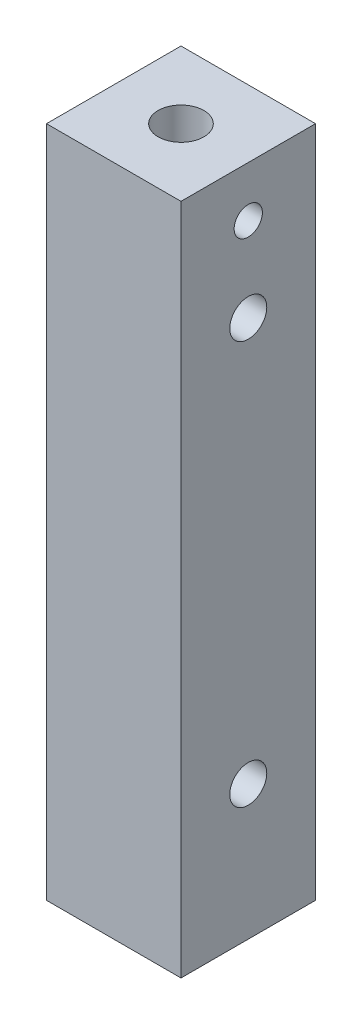
SolidWorks part; units mm, degrees
ref_plane "Front" through (0, 0, 0) normal (0, 0, 1) x (1, 0, 0)
ref_plane "Top" through (0, 0, 0) normal (0, 1, 0) x (1, 0, 0)
ref_plane "Right" through (0, 0, 0) normal (1, 0, 0) x (0, 0, -1)
sketch "Sketch1" plane through (0, 0, 0) normal (0, 1, 0) x (1, 0, 0)
  line L1 (0, 0) -> (20, 0)
  line L2 (0, 0) -> (0, 20)
  line L3 (0, 20) -> (20, 20)
  line L4 (20, 0) -> (20, 20)
  dimension "D1" = 20
  dimension "D2" = 20
extrude "Boss-Extrude1" add sketch "Sketch1" along normal blind 100
hole_wizard "M8 Tapped Hole1" positions "Sketch4" profile "Sketch5" tap size "M8" standard "ISO"
sketch "Sketch4" plane through (0, 100, 0) normal (0, 1, 0) x (1, 0, 0)
  line L0 (0, 20) -> (20, 0) construction
  line L2 (0, 0) -> (20, 20) construction
  point P13 (10, 10)
sketch "Sketch5" plane through (10, 100, -10) normal (1, 0, 0) x (0, 0, 1)
  line L0 (0, 0) -> (0, 15.7929)
  line L1 (0, 15.7929) -> (3.4, 13.75)
  line L2 (3.4, 13.75) -> (3.4, 0)
  line L5 (3.4, 0) -> (0, 0)
  line L10 (0, 15.7929) -> (-3.4, 13.75) construction
  line L11 (0, -6.35) -> (0, 107.95) construction
  dimension "Tap Drill Dia." = 6.8
  dimension "Tap Drill Depth" = 13.75
  dimension "Drill Angle" = 118
cosmetic thread "Hole Thread1"
ref_plane "Plane1" through (0, 50, 0) normal (0, 1, 0) x (1, 0, 0)
mirror "Mirror1" about plane through (0, 50, 0) normal (0, 1, 0) of "M8 Tapped Hole1"
cosmetic thread "Hole Thread2" parameters "D1"=16, "D2"=8
hole_wizard "M5 Tapped Hole1" [suppressed] positions "Sketch6" profile "Sketch7" tap size "M5" standard "ISO"
sketch "Sketch6" plane through (0, 0, 0) normal (0, 0, 1) x (1, 0, 0)
  line L0 (10, 100) -> (10, 95.0401) construction
  line L1 (0, 100) -> (20, 100) construction
  point P0 (10, 80)
  dimension "D1" = 20
sketch "Sketch7" plane through (10, 80, 0) normal (1, 0, 0) x (0, -1, 0)
  line L0 (0, 0) -> (0, 13.6618)
  line L1 (0, 13.6618) -> (2.1, 12.4)
  line L2 (2.1, 12.4) -> (2.1, 0)
  line L5 (2.1, 0) -> (0, 0)
  line L10 (0, 13.6618) -> (-2.1, 12.4) construction
  line L11 (0, -6.35) -> (0, 107.95) construction
  dimension "Tap Drill Dia." = 4.2
  dimension "Tap Drill Depth" = 12.4
  dimension "Drill Angle" = 118
cosmetic thread "Hole Thread3" [suppressed] parameters "D1"=10, "D2"=5
hole_wizard "M5 Tapped Hole2" [suppressed] positions "Sketch8" profile "Sketch9" tap size "M5" standard "ISO"
sketch "Sketch8" plane through (20, 0, 0) normal (1, 0, 0) x (0, 0, -1)
  line L0 (10, 0) -> (10, 26.2195) construction
  line L1 (0, 0) -> (20, 0) construction
  point P7 (10, 7.5)
  dimension "D1" = 7.5
sketch "Sketch9" plane through (20, 7.5, -10) normal (0, 1, 0) x (0, 0, -1)
  line L0 (0, 0) -> (0, 13.6618)
  line L1 (0, 13.6618) -> (2.1, 12.4)
  line L2 (2.1, 12.4) -> (2.1, 0)
  line L5 (2.1, 0) -> (0, 0)
  line L10 (0, 13.6618) -> (-2.1, 12.4) construction
  line L11 (0, -6.35) -> (0, 107.95) construction
  dimension "Tap Drill Dia." = 4.2
  dimension "Tap Drill Depth" = 12.4
  dimension "Drill Angle" = 118
cosmetic thread "Hole Thread4" [suppressed] parameters "D1"=10, "D2"=5
hole_wizard "M5 Clearance Hole1" positions "Sketch10" profile "Sketch12" hole size "M5" standard "ISO" end condition through all
sketch "Sketch10" plane through (20, 0, 0) normal (1, 0, 0) x (0, 0, -1)
  line L0 (10, 100) -> (10, 0) construction
  line L1 (0, 100) -> (20, 100) construction
  line L2 (0, 0) -> (20, 0) construction
  line L7 (0, 50) -> (20, 50) construction
  line L8 (0, 100) -> (0, 0) construction
  line L9 (20, 100) -> (20, 0) construction
  point P9 (10, 80)
  point P28 (10, 20)
  dimension "D1" = 20
sketch "Sketch12" plane through (20, 20, -10) normal (0, 1, 0) x (0, 0, -1)
  line L0 (0, 0) -> (0, 20)
  line L1 (0, 20) -> (2.75, 20)
  line L2 (2.75, 20) -> (2.75, 0)
  line L5 (2.75, 0) -> (0, 0)
  line L11 (0, -6.35) -> (0, 107.95) construction
  dimension "Thru Hole Dia." = 5.5
  dimension "Thru Hole Depth" = 20
hole_wizard "M5 Tapped Hole3" positions "Sketch13" profile "Sketch14" tap size "M5" standard "ISO"
sketch "Sketch13" plane through (20, 0, 0) normal (1, 0, 0) x (0, 0, -1)
  line L0 (10, 100) -> (10, 64.5146) construction
  line L1 (0, 100) -> (20, 100) construction
  circle A0 centre (10, 80) radius 2.75 construction
  point P7 (10, 92.5)
  dimension "D1" = 12.5
cosmetic thread "Hole Thread5"
sketch "Sketch14" plane through (20, 92.5, -10) normal (0, 1, 0) x (0, 0, -1)
  line L0 (0, 0) -> (0, 11.6618)
  line L1 (0, 11.6618) -> (2.1, 10.4)
  line L2 (2.1, 10.4) -> (2.1, 0)
  line L5 (2.1, 0) -> (0, 0)
  line L10 (0, 11.6618) -> (-2.1, 10.4) construction
  line L11 (0, -6.35) -> (0, 107.95) construction
  dimension "Tap Drill Dia." = 4.2
  dimension "Tap Drill Depth" = 10.4
  dimension "Drill Angle" = 118
